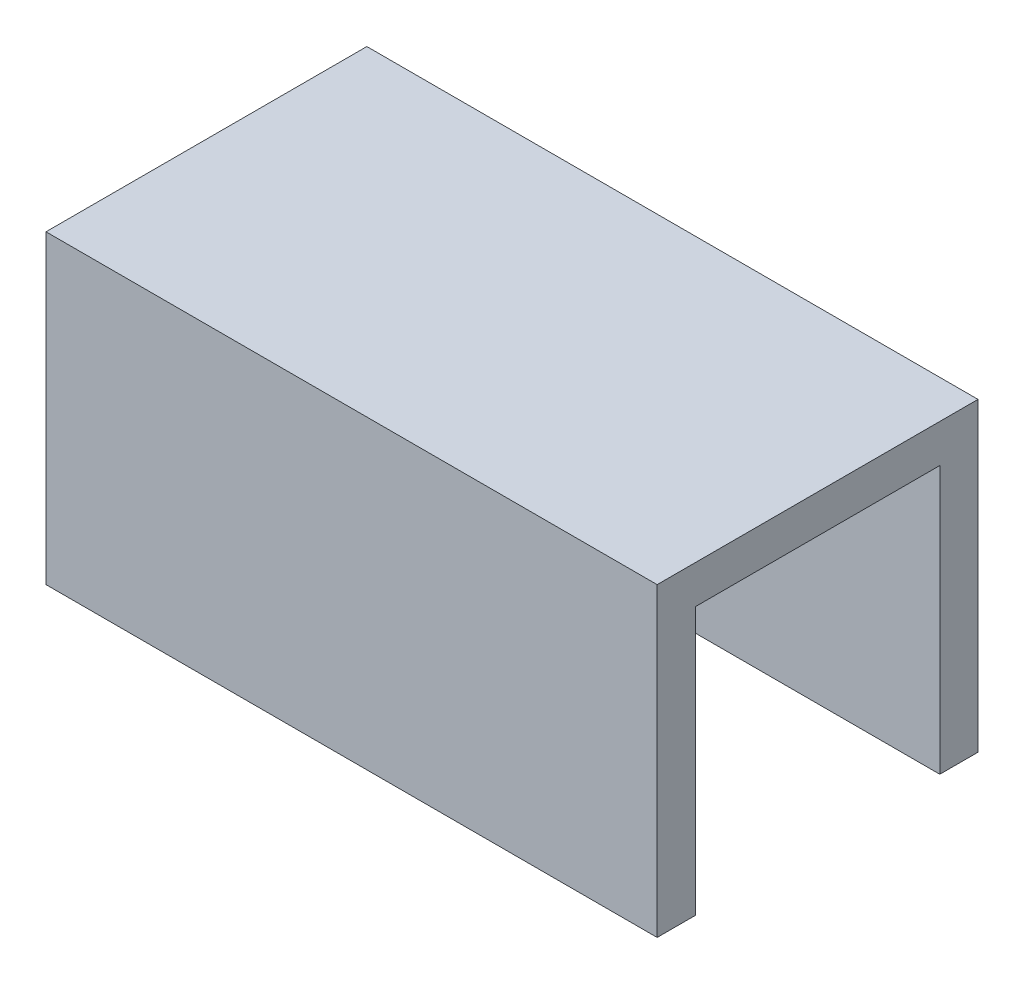
SolidWorks part; units mm, degrees
ref_plane "Front Plane" through (0, 0, 0) normal (0, 0, 1) x (1, 0, 0)
ref_plane "Top Plane" through (0, 0, 0) normal (0, 1, 0) x (1, 0, 0)
ref_plane "Right Plane" through (0, 0, 0) normal (1, 0, 0) x (0, 0, -1)
sketch "Sketch1" plane through (0, 0, 0) normal (1, 0, 0) x (0, 0, -1)
  line L0 (-8, 0) -> (-8, 17.5)
  line L1 (-8, 17.5) -> (8, 17.5)
  line L2 (8, 17.5) -> (8, 0)
  line L3 (8, 0) -> (10.5, 0)
  line L4 (10.5, 0) -> (10.5, 20)
  line L5 (10.5, 20) -> (-10.5, 20)
  line L6 (-10.5, 20) -> (-10.5, 0)
  line L7 (-10.5, 0) -> (-8, 0)
  point P3 (-9.9885, 3.752)
  point P9 (0, 20)
  point P10 (0, 17.5)
  point P13 (-9.9885, 3.0289)
  point P14 (-8, 0)
  point P15 (-8, 17.9477)
  dimension "D1" = 16
  dimension "D2" = 21
  dimension "D3" = 2.5
  dimension "D4" = 20
extrude "Boss-Extrude1" add sketch "Sketch1" along normal mid plane 40
sketch "Sketch2" plane through (0, 0, 8) normal (0, 0, -1) x (-1, 0, 0)
  line L1 (20, 0) -> (20, 20) construction
  line L3 (20, 17.5) -> (20, 20)
  line L5 (-20, 17.5) -> (-20, 20)
  line L6 (-20, 0) -> (-20, 20) construction
  line L7 (20, 20) -> (-20, 20)
  line L8 (-20, 17.5) -> (0, 0) construction
  line L9 (0, 0) -> (20, 17.5) construction
  arc A0 (-20, 17.5) -> (20, 17.5) centre (0, 40.3571) ccw
  point P0 (20, 19.4925)
  dimension "D1" = 2.5
extrude "Boss-Extrude2" add sketch "Sketch2" along normal up to next
